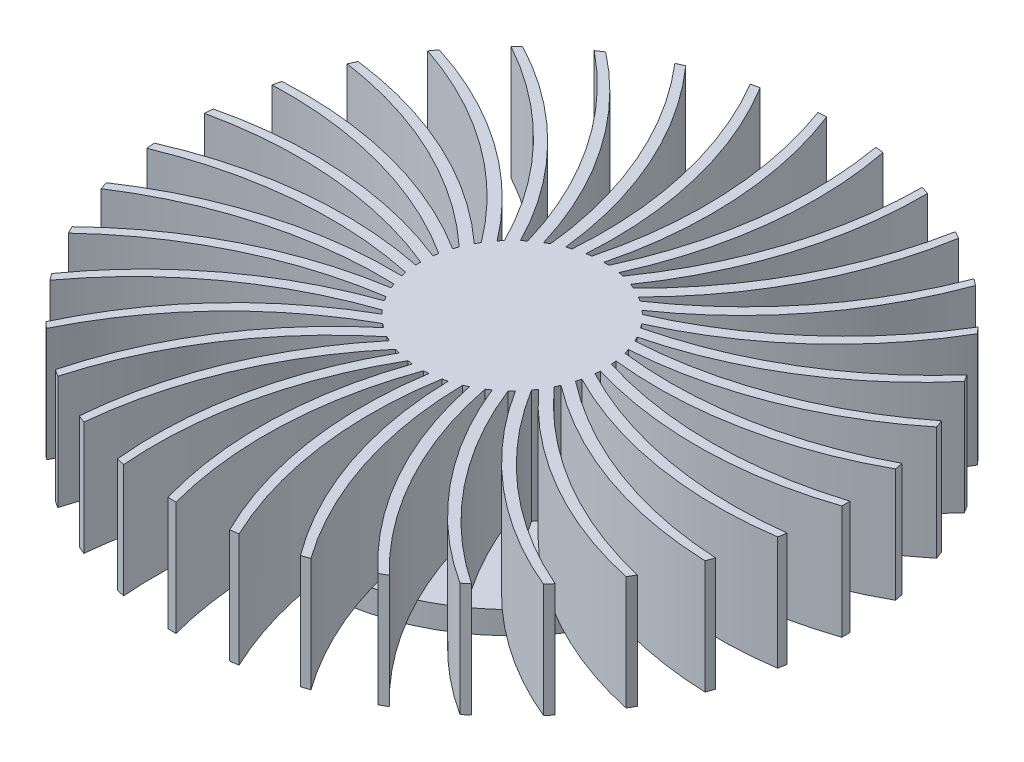
SolidWorks part; units mm, degrees
ref_plane "Front Plane" through (0, 0, 0) normal (0, 0, 1) x (1, 0, 0)
ref_plane "Top Plane" through (0, 0, 0) normal (0, 1, 0) x (1, 0, 0)
ref_plane "Right Plane" through (0, 0, 0) normal (1, 0, 0) x (0, 0, -1)
sketch "Sketch2" plane through (0, 1.905, 0) normal (0, 1, 0) x (1, 0, 0)
  circle A0 centre (0, 0) radius 17.5
  dimension "D1" = 35
extrude "Extrude1" add sketch "Sketch2" along normal blind 2
sketch "Sketch3" plane through (0, 3.905, 0) normal (0, 1, 0) x (1, 0, 0)
  circle A0 centre (0, 0) radius 28.9801
extrude "Extrude2" add sketch "Sketch3" along normal blind 10
sketch "Sketch4" plane through (0, 13.905, 0) normal (0, 1, 0) x (1, 0, 0)
  arc A0 (28.9801, 0) -> (8.0874, -0.3374) centre (18.0046, 32.5994) cw
  circle A1 centre (0, 0) radius 28.9801 construction
  arc A2 (28.635, -4.4593) -> (8.0561, -0.7869) centre (24.2015, 30.1918) cw
  arc A4 (28.635, -4.4593) -> (28.9801, 0) centre (0, 0) ccw
  arc A5 (8.0561, -0.7869) -> (8.0874, -0.3374) centre (0, 0) ccw
extrude "Cut-Extrude1" cut sketch "Sketch4" against normal blind 10
pattern_circular "CirPattern2" count 35 over 360 about axis through (0, 0, 0) along (0, 1, 0) of "Cut-Extrude1"
sketch "Sketch5" plane through (0, 1.905, 0) normal (0, -1, 0) x (1, 0, 0)
  line L0 (-10.946, -10.16) -> (-10.946, 10.16) construction
  line L1 (10.16, -10.946) -> (-10.16, -10.946) construction
  line L2 (10.946, 10.16) -> (10.946, -10.16) construction
  line L3 (-10.16, 10.946) -> (10.16, 10.946) construction
  line L4 (-10.946, -10.16) -> (-10.946, 10.16)
  line L5 (10.16, -10.946) -> (-10.16, -10.946)
  line L6 (10.946, 10.16) -> (10.946, -10.16)
  line L7 (-10.16, 10.946) -> (10.16, 10.946)
  arc A0 (-10.946, -10.16) -> (-10.16, -10.946) centre (-10.16, -10.16) ccw construction
  arc A1 (10.16, -10.946) -> (10.946, -10.16) centre (10.16, -10.16) ccw construction
  arc A2 (10.946, 10.16) -> (10.16, 10.946) centre (10.16, 10.16) ccw construction
  arc A3 (-10.946, -10.16) -> (-10.16, -10.946) centre (-10.16, -10.16) ccw
  arc A4 (10.16, -10.946) -> (10.946, -10.16) centre (10.16, -10.16) ccw
  arc A5 (10.946, 10.16) -> (10.16, 10.946) centre (10.16, 10.16) ccw
  arc A6 (-10.16, 10.946) -> (-10.946, 10.16) centre (-10.16, 10.16) ccw construction
  arc A7 (-10.16, 10.946) -> (-10.946, 10.16) centre (-10.16, 10.16) ccw
split line "Split Line1"
